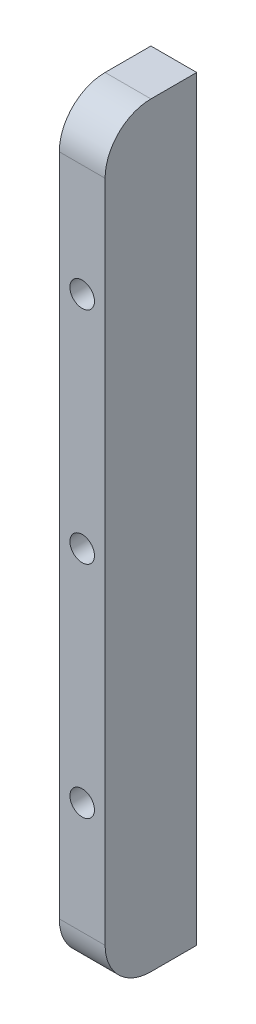
SolidWorks part; units mm, degrees
material "6061 Alloy"
ref_plane "Front Plane" through (0, 0, 0) normal (0, 0, 1) x (1, 0, 0)
ref_plane "Top Plane" through (0, 0, 0) normal (0, 1, 0) x (1, 0, 0)
ref_plane "Right Plane" through (0, 0, 0) normal (1, 0, 0) x (0, 0, -1)
sketch "Sketch1" plane through (0, 0, 0) normal (1, 0, 0) x (0, 0, -1)
  line L0 (-30.7474, -47.8589) -> (-30.7474, 56.9161)
  line L1 (-30.7474, 56.9161) -> (-43.4474, 56.9161)
  line L2 (-43.4474, 56.9161) -> (-43.4474, -47.8589)
  line L3 (-43.4474, -47.8589) -> (-30.7474, -47.8589)
  dimension "D1" = 104.775
  dimension "D2" = 12.7
extrude "Boss-Extrude1" add sketch "Sketch1" along normal blind 6.35
sketch "Sketch2" plane through (0, 0, 30.7474) normal (0, 0, -1) x (-1, 0, 0)
  line L0 (-6.35, 4.5286) -> (0, 4.5286)
  line L1 (-6.35, -47.8589) -> (-6.35, 56.9161) construction
  line L2 (-6.35, -16.4714) -> (0, -16.4714)
  line L3 (0, 6.985) -> (0, -6.985) construction
  line L4 (-6.35, 44.5786) -> (0, 44.5786)
  line L5 (-3.175, 4.5286) -> (-3.175, 13.5286)
  line L6 (-3.175, 13.5286) -> (-3.175, 25.5286)
  line L7 (-6.35, 25.5286) -> (0, 25.5286)
  line L8 (-3.175, 4.5286) -> (-3.175, -4.4714)
  line L9 (-3.175, -4.4714) -> (-3.175, -16.4714)
  line L11 (-6.35, -35.5214) -> (0, -35.5214)
  line L12 (0, 44.5786) -> (0, 25.5286)
  line L13 (0, 35.0536) -> (-6.35, 35.0536)
  line L14 (-6.35, -35.5214) -> (-6.35, -16.4714)
  line L15 (-6.35, -25.9964) -> (0, -25.9964)
  point P10 (-3.175, 4.5286)
  point P24 (-3.175, 35.0536)
  point P26 (-3.175, -25.9964)
  dimension "D1" = 9
  dimension "D2" = 12
  dimension "D3" = 19.05
  dimension "D4" = 9
  dimension "D5" = 12
  dimension "D6" = 19.05
hole_wizard "M3 Clearance Hole1" positions "Sketch2" profile "Sketch4" hole size "M3" standard "ANSI Metric" end condition through all
sketch "Sketch4" plane through (3.175, -25.9964, 30.7474) normal (1, 0, 0) x (0, 1, 0)
  line L0 (0, 0) -> (0, 12.7)
  line L1 (0, 12.7) -> (1.7, 12.7)
  line L2 (1.7, 12.7) -> (1.7, 0)
  line L5 (1.7, 0) -> (0, 0)
  line L11 (0, -6.35) -> (0, 107.95) construction
  dimension "Thru Hole Dia." = 3.4
  dimension "Thru Hole Depth" = 12.7
fillet "Fillet1" radius 6.35 2 edges at (3.175, -47.8589, 43.4474) (3.175, 56.9161, 43.4474)
